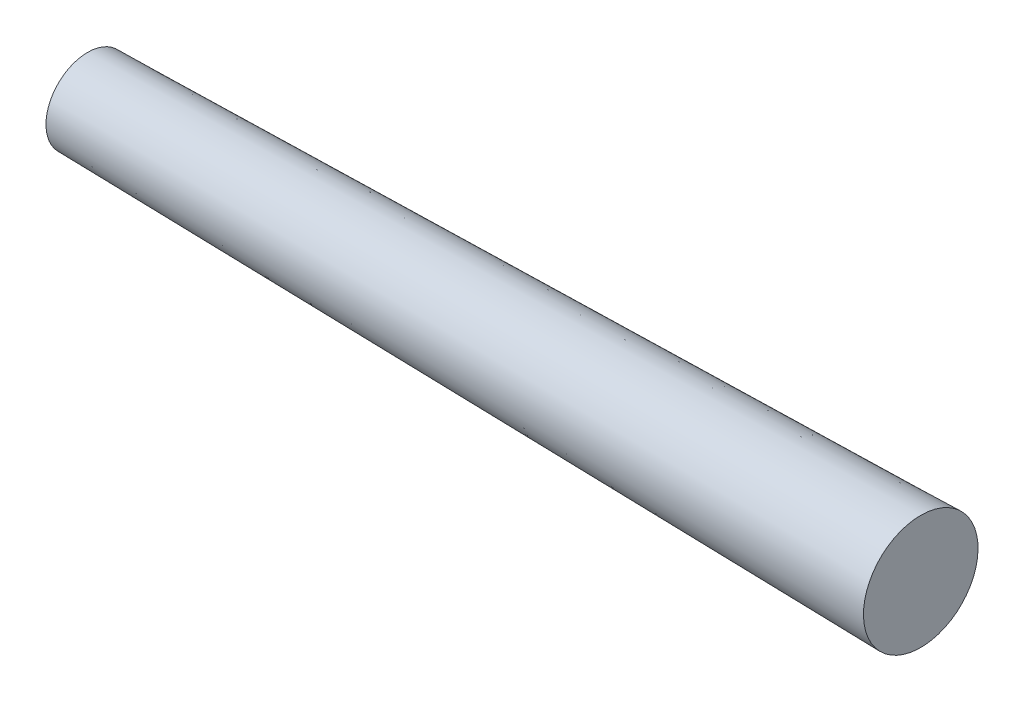
SolidWorks part; units mm, degrees
ref_plane "Ebene vorne" through (0, 0, 0) normal (0, 0, 1) x (1, 0, 0)
ref_plane "Ebene oben" through (0, 0, 0) normal (0, 1, 0) x (1, 0, 0)
ref_plane "Ebene rechts" through (0, 0, 0) normal (1, 0, 0) x (0, 0, -1)
sketch "Skizze1" plane through (0, 0, 0) normal (0, 0, 1) x (1, 0, 0)
  line L0 (-38.8804, 0) -> (-38.8804, 2.5)
  line L1 (-38.8804, 2.5) -> (-33.8804, 2.5)
  line L2 (-33.8804, 2.5) -> (-33.8804, 4)
  line L3 (-33.8804, 4) -> (46.1196, 5.5)
  line L4 (46.1196, 5.5) -> (46.1196, 4)
  line L5 (46.1196, 4) -> (51.1196, 4)
  line L6 (51.1196, 4) -> (51.1196, 0)
  line L7 (51.1196, 0) -> (-38.8804, 0)
  dimension "D1" = 90
  dimension "D2" = 5
  dimension "D3" = 5
  dimension "D4" = 1.5
  dimension "D5" = 1.5
  dimension "D6" = 2.5
  dimension "D7" = 4
revolve "Rotation1" add sketch "Skizze1" angle 360 about L7
sketch "Skizze2" plane through (-38.8804, 0, 0) normal (-1, 0, 0) x (0, 0, 1)
  circle A0 centre (0, 0) radius 2.5
extrude "Schnitt-Linear austragen1" cut sketch "Skizze2" against normal blind 5
sketch "Skizze3" plane through (51.1196, 0, 0) normal (1, 0, 0) x (0, 0, -1)
  circle A0 centre (0, 0) radius 4
extrude "Schnitt-Linear austragen2" cut sketch "Skizze3" against normal blind 5
